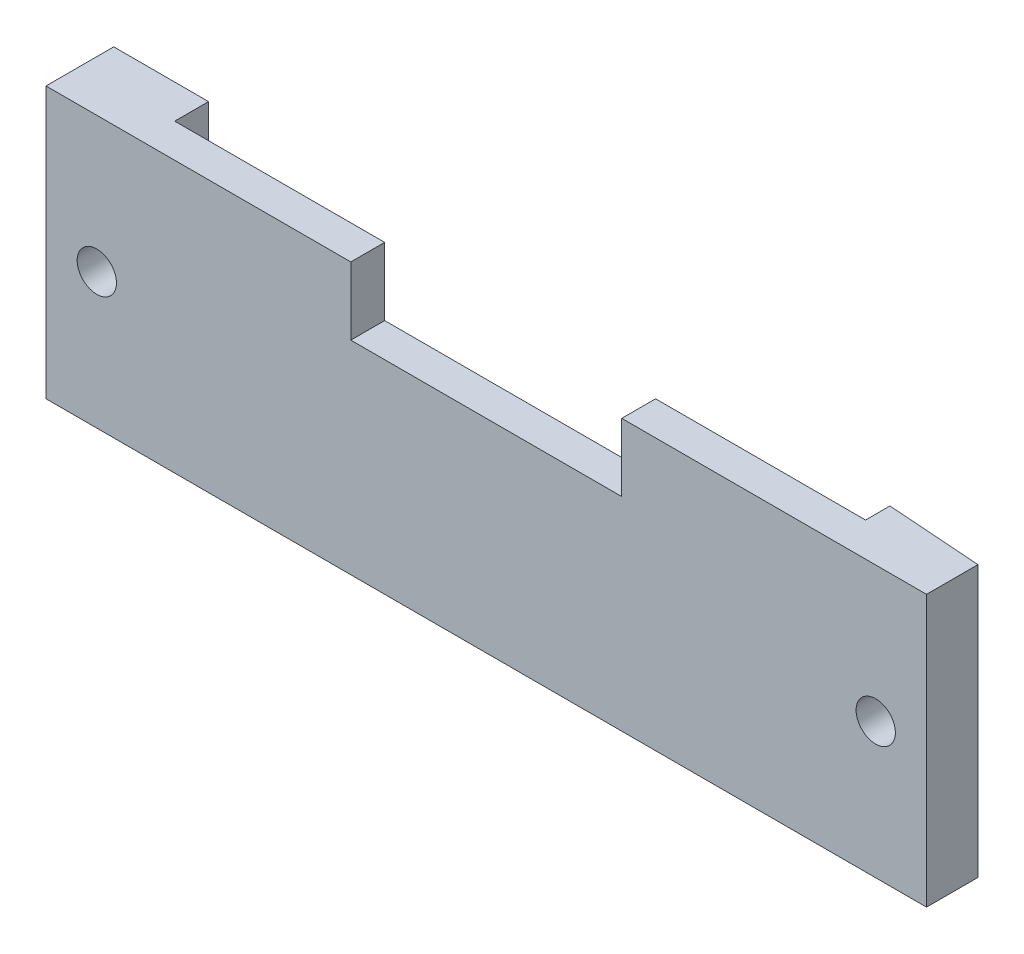
SolidWorks part; units mm, degrees
ref_plane "Front Plane" through (0, 0, 0) normal (0, 0, 1) x (1, 0, 0)
ref_plane "Top Plane" through (0, 0, 0) normal (0, 1, 0) x (1, 0, 0)
ref_plane "Right Plane" through (0, 0, 0) normal (1, 0, 0) x (0, 0, -1)
sketch "Sketch1" plane through (0, 0, 0) normal (0, 0, 1) x (1, 0, 0)
  line L0 (0, 0) -> (32.5, 0)
  line L1 (0, 0) -> (-32.5, 0)
  line L2 (-32.5, 0) -> (-32.5, 20)
  line L3 (32.5, 0) -> (32.5, 20)
  line L4 (32.5, 20) -> (-32.5, 20)
  dimension "D1" = 32.5
  dimension "D2" = 32.5
  dimension "D3" = 20
extrude "Boss-Extrude1" add sketch "Sketch1" along normal blind 5
sketch "Sketch2" plane through (0, 0, 0) normal (0, -1, 0) x (1, 0, 0)
  line L0 (-32.5, 0) -> (-25.5, 0) construction
  line L1 (-32.5, 0) -> (32.5, 0) construction
  line L2 (32.5, 0) -> (25.5, 0) construction
  line L3 (-25.5, 0) -> (-25.5, 2.5)
  line L5 (-25.5, 2.5) -> (25.5, 2.5)
  line L6 (25.5, 2.5) -> (25.5, 0)
  line L7 (25.5, 0) -> (-25.5, 0)
  dimension "D1" = 7
  dimension "D2" = 7
  dimension "D3" = 2.5
extrude "Cut-Extrude1" cut sketch "Sketch2" against normal up to next
sketch "Sketch3" plane through (0, 0, 5) normal (0, 0, 1) x (1, 0, 0)
  line L0 (-32.5, 10) -> (-25, 10) construction
  line L1 (-32.5, 20) -> (-32.5, 0) construction
  line L2 (32.5, 10) -> (25, 10) construction
  line L3 (32.5, 0) -> (32.5, 20) construction
  dimension "D1" = 7.5
  dimension "D2" = 7.5
hole_wizard "M3.5x0.6 Tapped Hole4" positions "Sketch10" profile "Sketch11" tap size "M3.5x0.6" standard "BSI" end condition up to next
sketch "Sketch10" plane through (0, 0, 5) normal (0, 0, 1) x (1, 0, 0)
  line L0 (-32.5, 10) -> (-25, 10) construction
  line L1 (32.5, 10) -> (25, 10) construction
  point P0 (-28.75, 10)
  point P4 (28.75, 10)
sketch "Sketch11" plane through (-28.75, 10, 5) normal (1, 0, 0) x (0, -1, 0)
  line L0 (0, 0) -> (0, 5)
  line L1 (0, 5) -> (1.45, 5)
  line L2 (1.45, 5) -> (1.45, 0)
  line L5 (1.45, 0) -> (0, 0)
  line L11 (0, -6.35) -> (0, 107.95) construction
  dimension "Thru Tap Drill Dia." = 2.9
  dimension "Thru Tap Drill Depth" = 5
cosmetic thread "Hole Thread3" parameters "D2"=3.5
cosmetic thread "Hole Thread4" parameters "D2"=3.5
sketch "Sketch12" plane through (0, 0, 5) normal (0, 0, 1) x (1, 0, 0)
  line L0 (0, 20) -> (-10, 20)
  line L1 (32.5, 20) -> (-32.5, 20) construction
  line L2 (0, 20) -> (10, 20)
  line L3 (-10, 20) -> (-10, 15)
  line L4 (-10, 15) -> (10, 15)
  line L5 (10, 15) -> (10, 20)
  dimension "D1" = 10
  dimension "D2" = 10
  dimension "D3" = 5
extrude "Cut-Extrude2" cut sketch "Sketch12" against normal up to next
sketch "Sketch13" plane through (0, 0, 0) normal (0, -1, 0) x (1, 0, 0)
  line L0 (25.5, 0) -> (25.5, 0.7)
  line L1 (25.5, 0) -> (25.5, 2.5) construction
  line L2 (32.5, 0) -> (32.5, 1.2)
  line L3 (32.5, 5) -> (32.5, 0) construction
  line L4 (25.5, 0) -> (32.5, 0)
  line L5 (25.5, 0.7) -> (32.5, 1.2)
  dimension "D1" = 0.7
  dimension "D2" = 1.2
extrude "Cut-Extrude3" cut sketch "Sketch13" against normal up to next
